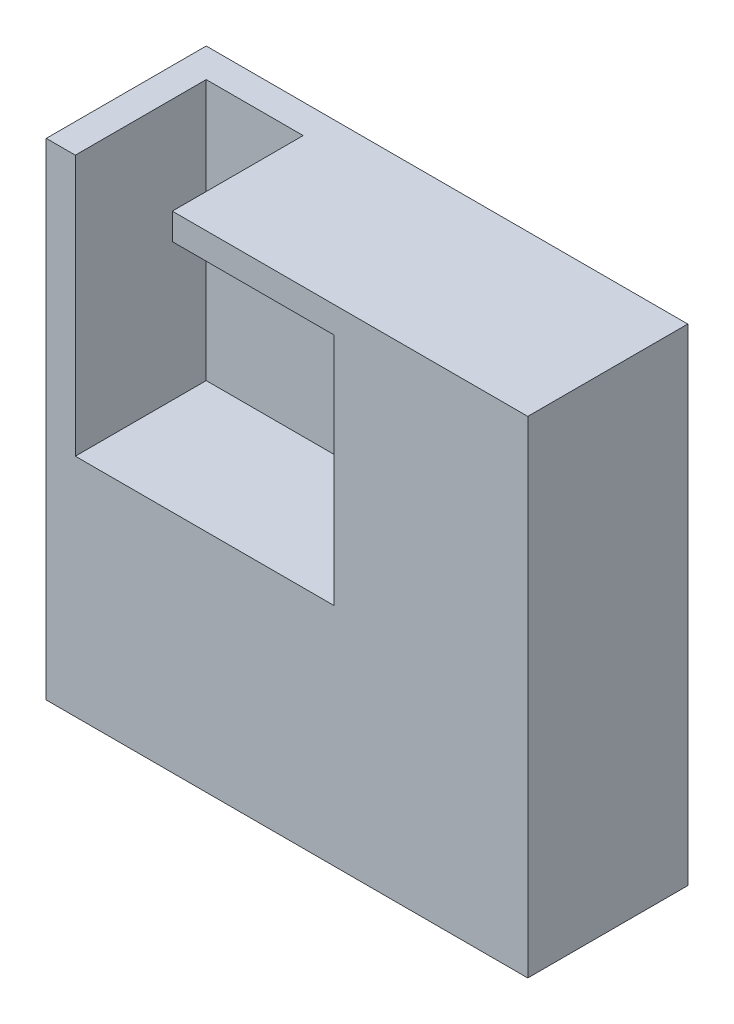
SolidWorks part; units mm, degrees
ref_plane "Front Plane" through (0, 0, 0) normal (0, 0, 1) x (1, 0, 0)
ref_plane "Top Plane" through (0, 0, 0) normal (0, 1, 0) x (1, 0, 0)
ref_plane "Right Plane" through (0, 0, 0) normal (1, 0, 0) x (0, 0, -1)
sketch "Sketch1" plane through (0, 0, 0) normal (0, 0, 1) x (1, 0, 0)
  line L1 (0, 0) -> (29.8, 0)
  line L2 (0, 0) -> (0, 30.1)
  line L3 (0, 30.1) -> (29.8, 30.1)
  line L4 (29.8, 0) -> (29.8, 30.1)
  dimension "D1" = 29.8
  dimension "D2" = 30.1
extrude "Boss-Extrude1" add sketch "Sketch1" along normal blind 9.9
sketch "Sketch2" plane through (0, 0, 9.9) normal (0, 0, 1) x (1, 0, 0)
  line L0 (0, 30.1) -> (0, 0) construction
  line L1 (7.8, 30.1) -> (7.8, 28.4669)
  line L2 (7.8, 28.4669) -> (17.8, 28.4669)
  line L4 (1.8, 28.4669) -> (1.8, 13.9669)
  line L5 (1.8, 13.9669) -> (17.8, 13.9669)
  line L6 (17.8, 28.4669) -> (17.8, 13.9669)
  line L7 (1.8, 28.4669) -> (1.8, 30.1)
  line L8 (29.8, 30.1) -> (0, 30.1) construction
  line L9 (1.8, 30.1) -> (7.8, 30.1)
  dimension "D1" = 16
  dimension "D2" = 14.5
  dimension "D3" = 1.8
  dimension "D4" = 6
extrude "Cut-Extrude1" cut sketch "Sketch2" against normal blind 8.1
sketch "Sketch3" plane through (0, 0, 1.8) normal (0, 0, 1) x (1, 0, 0)
  line L1 (1.8, 13.9669) -> (17.8, 13.9669) construction
  line L2 (17.8, 13.9669) -> (17.8, 28.4669) construction
  circle A0 centre (14.3, 17.4669) radius 2.8
  dimension "D2" = 3.5
  dimension "D3" = 5.6
  dimension "D1" = 3.5
extrude "Cut-Extrude2" cut sketch "Sketch3" against normal through all
